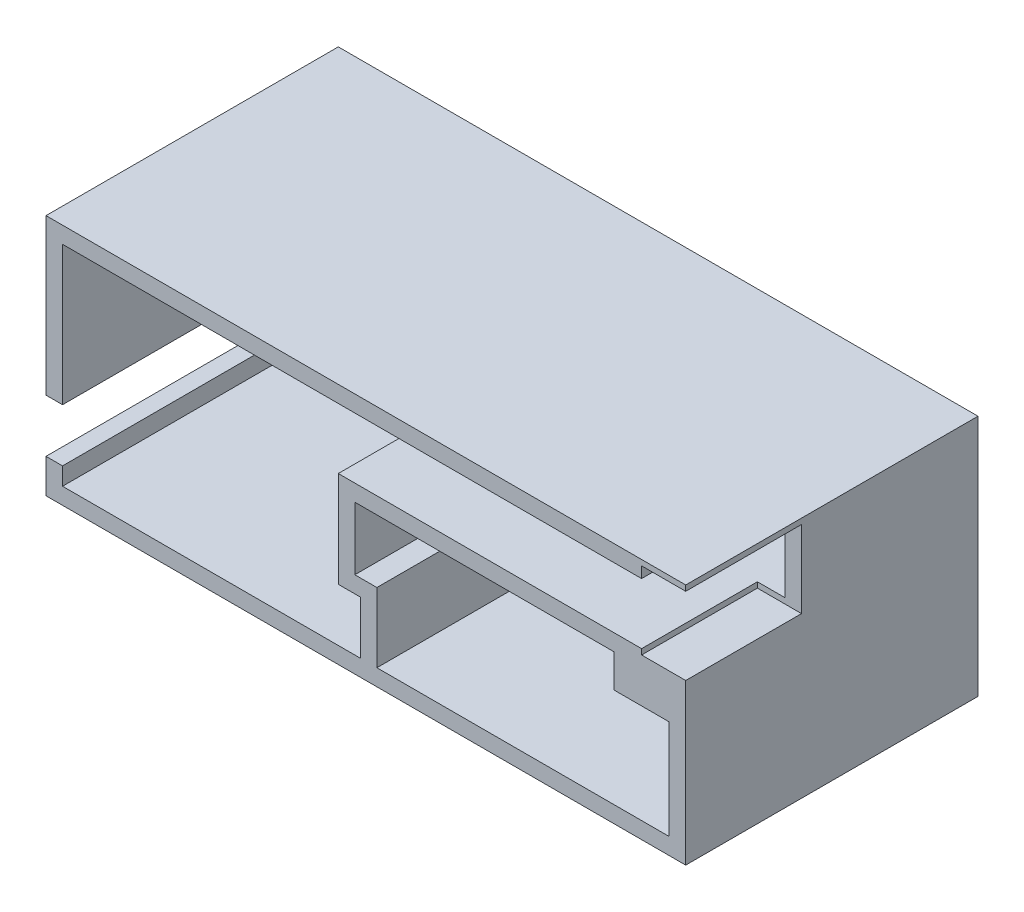
SolidWorks part; units mm, degrees
ref_plane "Front Plane" through (0, 0, 0) normal (0, 0, 1) x (1, 0, 0)
ref_plane "Top Plane" through (0, 0, 0) normal (0, 1, 0) x (1, 0, 0)
ref_plane "Right Plane" through (0, 0, 0) normal (1, 0, 0) x (0, 0, -1)
sketch "Sketch1" plane through (0, 0, 0) normal (0, 0, 1) x (1, 0, 0)
  line L0 (-44.6807, 0) -> (45.937, 0) construction
  line L2 (-19.2815, 0) -> (38.7185, 0)
  line L3 (-19.2815, 0) -> (-19.2815, 22)
  line L4 (-19.2815, 22) -> (38.7185, 22)
  line L5 (38.7185, 0) -> (38.7185, 22)
  dimension "D1" = 58
  dimension "D2" = 22
extrude "Boss-Extrude1" add sketch "Sketch1" along normal blind 1.5
sketch "Sketch2" plane through (0, 0, 1.5) normal (0, 0, 1) x (1, 0, 0)
  line L4 (-17.7815, 20.5) -> (-17.7815, 1.5)
  line L5 (-17.7815, 1.5) -> (9.2185, 1.5)
  line L6 (37.2185, 1.5) -> (37.2185, 10.5)
  line L7 (37.2185, 20.5) -> (-17.7815, 20.5)
  line L8 (-19.2815, 22) -> (-19.2815, 0)
  line L9 (-19.2815, 0) -> (38.7185, 0)
  line L10 (38.7185, 0) -> (38.7185, 22)
  line L11 (38.7185, 22) -> (-19.2815, 22)
  line L12 (-19.2815, 22) -> (-19.2815, 0)
  line L13 (-19.2815, 0) -> (38.7185, 0)
  line L14 (38.7185, 0) -> (38.7185, 22)
  line L15 (38.7185, 22) -> (-19.2815, 22)
  line L16 (-17.7815, 6.3) -> (9.2185, 6.3) construction
  line L17 (-17.7815, 15) -> (37.2185, 15) construction
  line L18 (37.2185, 15) -> (7.2185, 15)
  line L19 (7.2185, 15) -> (7.2185, 6.3)
  line L20 (7.2185, 6.3) -> (9.2185, 6.3)
  line L21 (9.2185, 6.3) -> (9.2185, 1.5)
  line L22 (32.2185, 13.5) -> (8.7185, 13.5)
  line L23 (8.7185, 13.5) -> (8.7185, 7.8)
  line L24 (8.7185, 7.8) -> (10.7185, 7.8)
  line L25 (10.7185, 7.8) -> (10.7185, 1.5)
  line L26 (37.2185, 15) -> (37.2185, 20.5)
  line L27 (37.2185, 1.5) -> (37.2185, 20.5) construction
  line L28 (10.7185, 1.5) -> (37.2185, 1.5)
  line L29 (-17.7815, 1.5) -> (37.2185, 1.5) construction
  line L30 (32.2185, 13.5) -> (32.2185, 10.5)
  line L31 (32.2185, 10.5) -> (37.2185, 10.5)
  line L32 (37.2185, 13.5) -> (8.7185, 13.5) construction
  dimension "D3" = 4.8
  dimension "D4" = 5.5
  dimension "D5" = 30
  dimension "D6" = 27
  dimension "D8" = 3
  dimension "D9" = 5
  dimension "D1" = 0
  dimension "D2" = 1.5
  dimension "D7" = 1.5
extrude "Boss-Extrude2" add sketch "Sketch2" along normal blind 25
sketch "Sketch3" plane through (-19.2815, 0, 0) normal (-1, 0, 0) x (0, 0, 1)
  line L0 (0, 5.5) -> (26.5, 5.5) construction
  line L1 (0, 22) -> (0, 0) construction
  line L2 (26.5, 22) -> (26.5, 0) construction
  line L3 (26.5, 0) -> (0, 0) construction
  line L4 (7.25, 3.1) -> (19.25, 3.1)
  line L5 (7.25, 3.1) -> (7.25, 7.9)
  line L6 (7.25, 7.9) -> (19.25, 7.9)
  line L8 (7.25, 3.1) -> (19.25, 7.9) construction
  line L9 (7.25, 7.9) -> (19.25, 3.1) construction
  line L10 (19.25, 7.9) -> (26.5, 7.9)
  line L11 (19.25, 3.1) -> (26.5, 3.1)
  line L12 (26.5, 7.9) -> (26.5, 3.1)
  point P6 (13.25, 5.5)
  dimension "D1" = 4.8
  dimension "D2" = 12
  dimension "D3" = 5.5
extrude "Cut-Extrude1" cut sketch "Sketch3" against normal blind 5
sketch "Sketch6" plane through (38.7185, 0, 0) normal (1, 0, 0) x (0, 0, -1)
  line L0 (-26.5, 18) -> (0, 18) construction
  line L1 (-26.5, 0) -> (-26.5, 22) construction
  line L2 (0, 0) -> (0, 22) construction
  line L3 (-26.5, 22) -> (0, 22) construction
  line L7 (-26.5, 21.5) -> (-16, 21.5)
  line L8 (-16, 21.5) -> (-16, 14.5)
  line L9 (-16, 14.5) -> (-26.5, 14.5)
  line L10 (-26.5, 21.5) -> (-26.5, 14.5)
  dimension "D1" = 7
  dimension "D2" = 4
  dimension "D3" = 3.5
  dimension "D4" = 16
extrude "Cut-Extrude2" cut sketch "Sketch6" against normal blind 4
